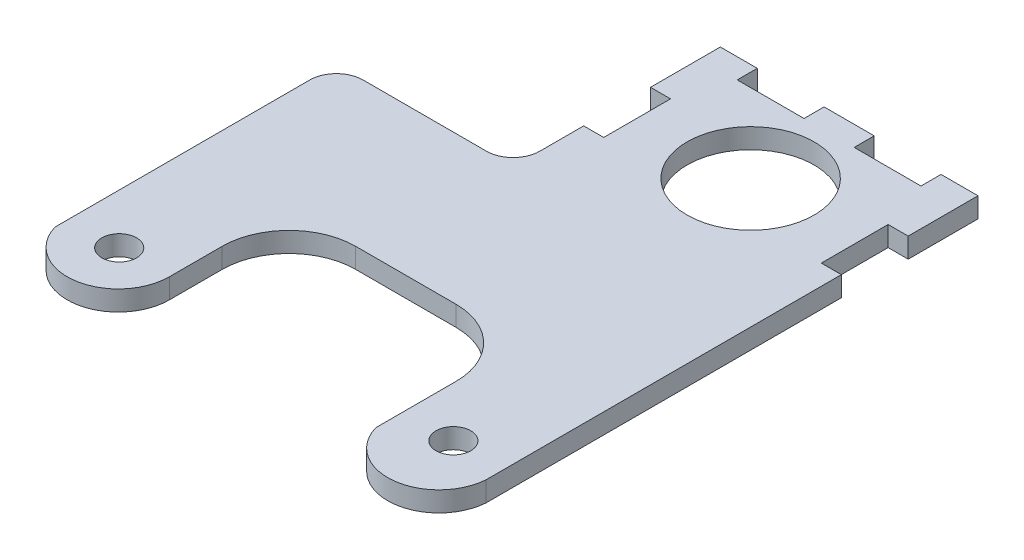
SolidWorks part; units mm, degrees
ref_plane "Front Plane" through (0, 0, 0) normal (0, 0, 1) x (1, 0, 0)
ref_plane "Top Plane" through (0, 0, 0) normal (0, 1, 0) x (1, 0, 0)
ref_plane "Right Plane" through (0, 0, 0) normal (1, 0, 0) x (0, 0, -1)
sketch "Sketch1" plane through (0, 0, 0) normal (0, 1, 0) x (1, 0, 0)
  line L0 (-25, -32.3319) -> (25, -32.3319) construction
  line L1 (-32.5, -42.3319) -> (32.5, -42.3319)
  line L2 (-32.5, -42.3319) -> (-32.5, -1.3319)
  line L4 (32.5, -42.3319) -> (32.5, -1.3319)
  line L5 (-32.5, -42.3319) -> (9.7258, 12.6681) construction
  line L6 (-6.0586, 7.8915) -> (32.5, -42.3319) construction
  line L7 (-32.5, 12.6681) -> (9.7258, 12.6681) construction
  line L8 (-7.5, -14.4422) -> (7.5, -14.4422)
  line L9 (-32.5, -42.3319) -> (-17.5, -42.3319)
  line L10 (-32.5, -42.3319) -> (-32.5, 3.1015)
  line L12 (-17.5, -42.3319) -> (-17.5, -24.4422)
  line L14 (17.5, -24.4422) -> (17.5, -42.3319)
  line L15 (17.5, -42.3319) -> (32.5, -42.3319)
  line L16 (32.5, -1.3319) -> (32.5, -42.3319)
  line L17 (32.4414, 38.6681) -> (32.5, 38.6681)
  line L18 (-6.0586, 38.6681) -> (-6.0586, 11.6681)
  line L19 (-6.0586, 38.6681) -> (32.4414, 38.6681)
  line L20 (-6.0586, 38.6681) -> (-6.0586, 11.6681)
  line L22 (32.4414, 38.6681) -> (32.4414, 11.8397)
  line L23 (-6.0586, 38.6681) -> (0.4668, 33.6681) construction
  line L25 (32.5, -1.3319) -> (32.5, 3.6681)
  line L26 (32.5, 38.6681) -> (32.5, -33.8319)
  line L27 (-1.5042, 23.898) -> (8.3443, 23.898) construction
  line L30 (-1.5586, 33.6681) -> (0.4668, 33.6681)
  line L32 (-7.6586, 9.9754) -> (-3.6156, 12.6681) construction
  line L33 (5.3156, 29.1289) -> (16.6325, 21.6641) construction
  line L34 (8.3443, 23.898) -> (8.3443, 32.0359) construction
  line L35 (1.5292, 16.0946) -> (1.9563, 16.4218) construction
  line L36 (5.6946, 29.6624) -> (16.4475, 21.4232) construction
  line L37 (-7.2135, 9.3957) -> (-2.9427, 12.6681) construction
  line L38 (-10.8774, 14.1681) -> (-6.0586, 14.1681)
  line L39 (27.8736, 12.6681) -> (31.0947, 10.1999) construction
  line L40 (27.8736, 12.6681) -> (32.4414, 12.6681) construction
  line L41 (16.4475, 21.4232) -> (16.6325, 21.6641) construction
  line L42 (-32.5, -1.3319) -> (-32.5, 3.6681)
  line L43 (19.4512, 25.3356) -> (19.7141, 25.678) construction
  line L44 (-28.5, 7.6681) -> (-10.0586, 7.6681)
  line L45 (-1.5586, 23.898) -> (22.7458, 23.898) construction
  line L46 (5.1745, 18.8877) -> (20.1834, 30.388) construction
  line L47 (5.339, 18.6319) -> (24.473, 31.3754) construction
  line L49 (27.9414, 23.898) -> (32.4414, 23.898) construction
  line L50 (1.5292, 16.0946) -> (1.9849, 16.3981) construction
  circle A0 centre (-25, -32.3319) radius 2.6
  circle A1 centre (25, -32.3319) radius 2.6
  arc A2 (17.5, -32.3319) -> (32.5, -33.8319) centre (24.8707, -34.3745) ccw
  arc A3 (-32.5, -34.437) -> (-17.5, -32.3319) centre (-25.1485, -32.3262) ccw
  circle A4 centre (13.2458, 23.898) radius 9.5
  arc A5 (1.9563, 16.4218) -> (1.9849, 16.3981) centre (8.1926, 23.9181) ccw
  arc A8 (17.5, -24.4422) -> (7.5, -14.4422) centre (7.5, -24.4422) ccw
  arc A9 (-7.5, -14.4422) -> (-17.5, -24.4422) centre (-7.5, -24.4422) ccw
  arc A12 (-6.0586, 11.6681) -> (-10.0586, 7.6681) centre (-10.0586, 11.6681) cw
  arc A13 (-28.5, 7.6681) -> (-32.5, 3.6681) centre (-28.5, 3.6681) ccw
  point P0 (0, 0)
  point P1 (13.2458, 23.898)
  point P10 (0, -32.3319)
  point P27 (12.4655, 24.4743)
  dimension "D4" = 5.2
  dimension "D2" = 19
  dimension "D10" = 10
  dimension "D11" = 4
  dimension "D3" = 50
  dimension "D5" = 55
  dimension "D6" = 45
  dimension "D7" = 7.5
  dimension "D8" = 38.5
  dimension "D13" = 28.5
  dimension "D15" = 5
  dimension "D16" = 7.5
  dimension "D17" = 7.5
extrude "Boss-Extrude1" add sketch "Sketch1" along normal blind 3
sketch "Sketch2" plane through (0, 3, 0) normal (0, 1, 0) x (1, 0, 0)
  line L0 (-6.0586, 38.6681) -> (32.5, 38.6681) construction
  line L5 (9.4707, 37.1681) -> (16.9707, 37.1681) construction
  line L6 (-0.5293, 38.6681) -> (9.4707, 38.6681)
  line L7 (-0.5293, 38.6681) -> (-0.5293, 35.6681)
  line L8 (-0.5293, 35.6681) -> (9.4707, 35.6681)
  line L9 (9.4707, 38.6681) -> (9.4707, 35.6681)
  line L10 (-6.0586, 38.6681) -> (-6.0586, 11.6681) construction
  line L11 (-6.0586, 28.2206) -> (-3.0586, 28.2206)
  line L12 (-6.0586, 28.2206) -> (-6.0586, 18.2206)
  line L13 (-6.0586, 18.2206) -> (-3.0586, 18.2206)
  line L14 (-3.0586, 28.2206) -> (-3.0586, 18.2206)
  line L21 (-6.0586, 38.6681) -> (32.5, 38.6681) construction
  line L22 (26.9707, 38.6681) -> (16.9707, 38.6681)
  line L23 (26.9707, 38.6681) -> (26.9707, 35.6681)
  line L24 (26.9707, 35.6681) -> (16.9707, 35.6681)
  line L25 (16.9707, 38.6681) -> (16.9707, 35.6681)
  line L27 (32.5, -34.9171) -> (32.5, 38.6681) construction
  line L28 (32.5, 18.2206) -> (29.5, 18.2206)
  line L29 (32.5, 18.2206) -> (32.5, 28.2206)
  line L30 (32.5, 28.2206) -> (29.5, 28.2206)
  line L31 (29.5, 18.2206) -> (29.5, 28.2206)
  line L33 (-6.0586, 31.5454) -> (32.5, 31.5454) construction
  line L34 (-6.0586, 38.6681) -> (-6.0586, 11.6681) construction
  point P2 (13.2207, 38.6681)
  point P3 (13.2207, 37.1681)
  point P23 (13.2207, 31.5454)
  point P25 (16.9707, 37.1681)
  dimension "D1" = 10
  dimension "D2" = 3
  dimension "D3" = 10
  dimension "D4" = 3
  dimension "D5" = 3
  dimension "D6" = 3
  dimension "D7" = 10
  dimension "D8" = 7.4475
  dimension "D9" = 7.5
extrude "Cut-Extrude1" cut sketch "Sketch2" against normal blind 3
